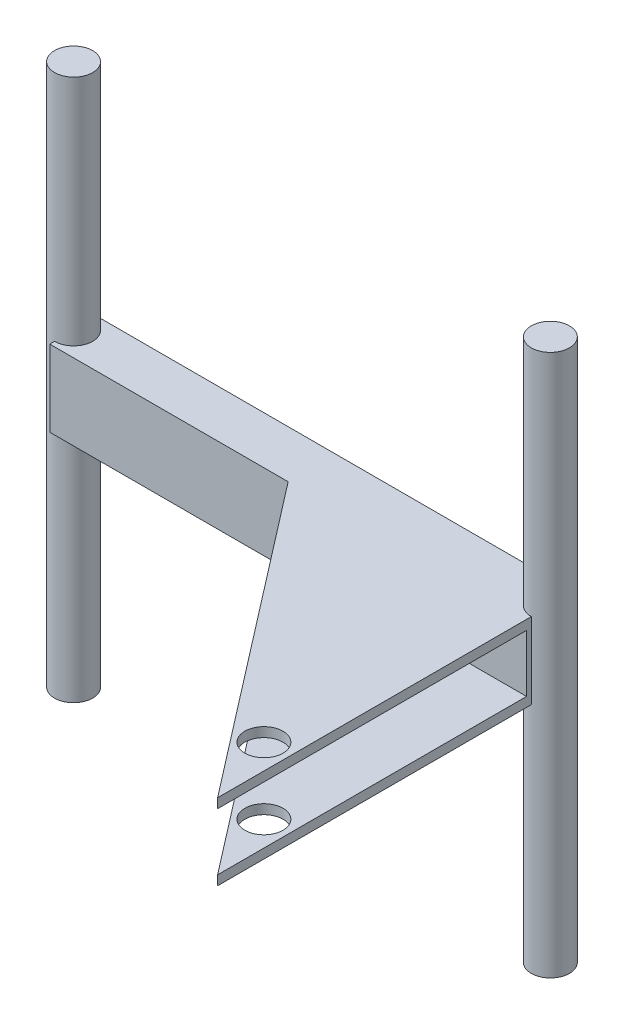
SolidWorks part; units mm, degrees
ref_plane "Front Plane" through (0, 0, 0) normal (0, 0, 1) x (1, 0, 0)
ref_plane "Top Plane" through (0, 0, 0) normal (0, 1, 0) x (1, 0, 0)
ref_plane "Right Plane" through (0, 0, 0) normal (1, 0, 0) x (0, 0, -1)
sketch "Sketch1" plane through (0, 0, 0) normal (0, 0, 1) x (1, 0, 0)
  line L1 (-158.5903, 43.7775) -> (341.4097, 43.7775)
  line L2 (-158.5903, 43.7775) -> (-158.5903, -36.2225)
  line L3 (-158.5903, -36.2225) -> (341.4097, -36.2225)
  line L4 (341.4097, 43.7775) -> (341.4097, -36.2225)
  dimension "D1" = 500
  dimension "D2" = 80
extrude "Boss-Extrude1" add sketch "Sketch1" along normal blind 50
sketch "Sketch2" plane through (0, 43.7775, 0) normal (0, 1, 0) x (1, 0, 0)
  line L0 (-158.5903, -50) -> (-158.5903, 0) construction
  line L1 (341.4097, -50) -> (341.4097, 0) construction
  circle A0 centre (-158.5903, -25) radius 20
  circle A1 centre (341.4097, -25) radius 20
extrude "Boss-Extrude2" add sketch "Sketch2" along normal blind 244.1 and the other way blind 324.1
sketch "Sketch5" plane through (0, -36.2225, 0) normal (0, -1, 0) x (-1, 0, 0)
  line L0 (-341.4097, -50) -> (-341.4097, -374)
  line L1 (-341.4097, -374) -> (-91.4097, -50)
  line L2 (158.5903, -50) -> (-341.4097, -50) construction
  line L3 (-91.4097, -50) -> (-341.4097, -50)
  dimension "D1" = 324
extrude "Boss-Extrude5" add sketch "Sketch5" against normal blind 10
sketch "Sketch6" plane through (0, 43.7775, 0) normal (0, 1, 0) x (1, 0, 0)
  line L0 (341.4097, -50) -> (91.4097, -50)
  line L1 (341.4097, -50) -> (-158.5903, -50) construction
  line L2 (91.4097, -50) -> (341.4097, -374)
  line L3 (341.4097, -374) -> (341.4097, -50)
extrude "Boss-Extrude6" add sketch "Sketch6" against normal blind 10
sketch "Sketch7" plane through (0, -36.2225, 0) normal (0, -1, 0) x (-1, 0, 0)
  circle A1 centre (-315.2492, -299.2496) radius 20
extrude "Cut-Extrude4" cut sketch "Sketch7" against normal through all both and the other way through all contours A1
